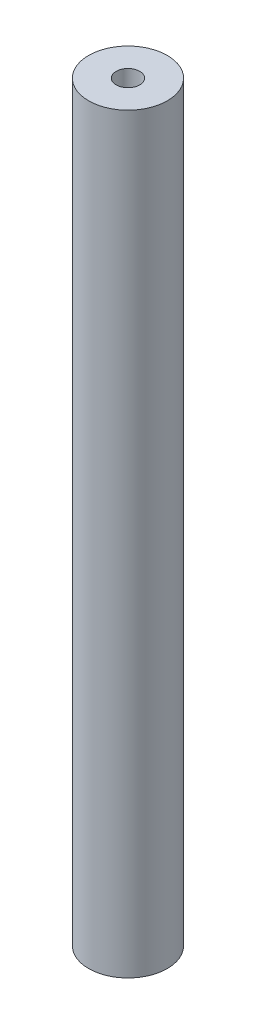
SolidWorks part; units mm, degrees
ref_plane "Front Plane" through (0, 0, 0) normal (0, 0, 1) x (1, 0, 0)
ref_plane "Top Plane" through (0, 0, 0) normal (0, 1, 0) x (1, 0, 0)
ref_plane "Right Plane" through (0, 0, 0) normal (1, 0, 0) x (0, 0, -1)
sketch "Sketch1" plane through (0, 0, 0) normal (0, 1, 0) x (1, 0, 0)
  circle A0 centre (0, 0) radius 0.9
  circle A1 centre (0, 0) radius 3
  dimension "D1" = 1.8
  dimension "D2" = 6
extrude "Boss-Extrude1" add sketch "Sketch1" along normal blind 57.33
